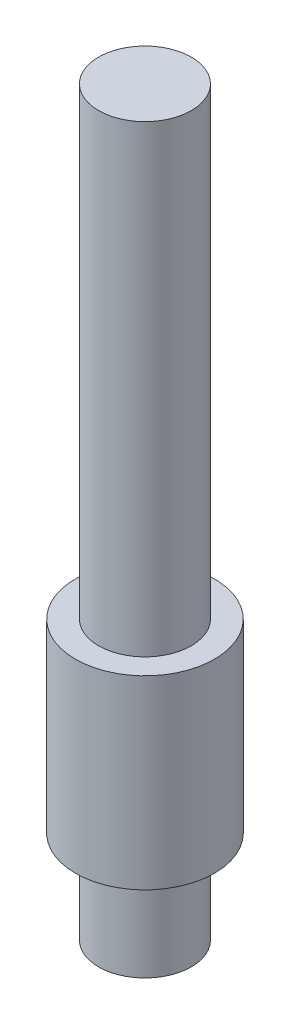
SolidWorks part; units mm, degrees
ref_plane "Ön Düzlem" through (0, 0, 0) normal (0, 0, 1) x (1, 0, 0)
ref_plane "Üst Düzlem" through (0, 0, 0) normal (0, 1, 0) x (1, 0, 0)
ref_plane "Sağ Düzlem" through (0, 0, 0) normal (1, 0, 0) x (0, 0, -1)
sketch "Sketch1" plane through (0, 0, 0) normal (0, 0, 1) x (1, 0, 0)
  line L0 (0, 39.9879) -> (0, -17.0064) construction
  line L1 (15, 60) -> (15, 20)
  line L2 (15, 20) -> (10, 20)
  line L3 (10, 20) -> (10, 0)
  line L4 (10, 0) -> (0, 0)
  line L5 (15, 60) -> (10, 60)
  line L6 (10, 60) -> (10, 160)
  line L7 (0, 0) -> (0, 160)
  line L11 (10, 160) -> (0, 160)
  dimension "D1" = 15
  dimension "D2" = 10
  dimension "D3" = 40
  dimension "D4" = 20
  dimension "D5" = 100
revolve "Revolve1" add sketch "Sketch1" angle 360 about L0
